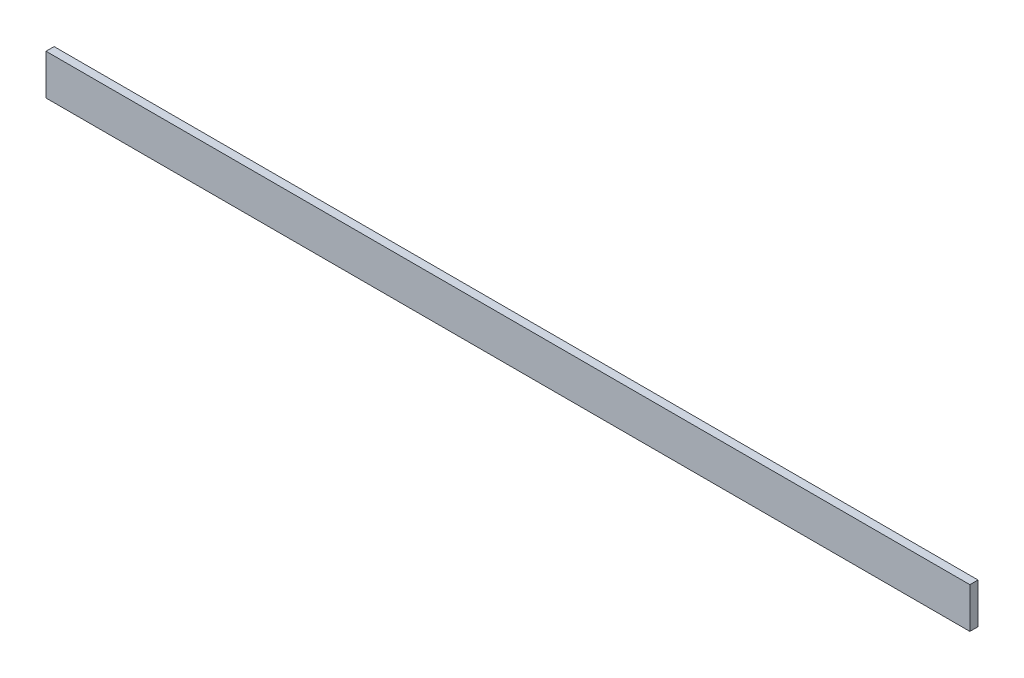
SolidWorks part; units mm, degrees
ref_plane "前视基准面" through (0, 0, 0) normal (0, 0, 1) x (1, 0, 0)
ref_plane "上视基准面" through (0, 0, 0) normal (0, 1, 0) x (1, 0, 0)
ref_plane "右视基准面" through (0, 0, 0) normal (1, 0, 0) x (0, 0, -1)
sketch "草图1" plane through (0, 0, 0) normal (0, 0, 1) x (1, 0, 0)
  line L1 (-57, -2.5) -> (57, -2.5)
  line L2 (-57, -2.5) -> (-57, 2.5)
  line L3 (-57, 2.5) -> (57, 2.5)
  line L4 (57, -2.5) -> (57, 2.5)
  line L5 (-57, -2.5) -> (57, 2.5) construction
  line L6 (-57, 2.5) -> (57, -2.5) construction
  point P0 (0, 0)
  dimension "D1" = 114
  dimension "D2" = 5
extrude "凸台-拉伸1" add sketch "草图1" along normal blind 1
